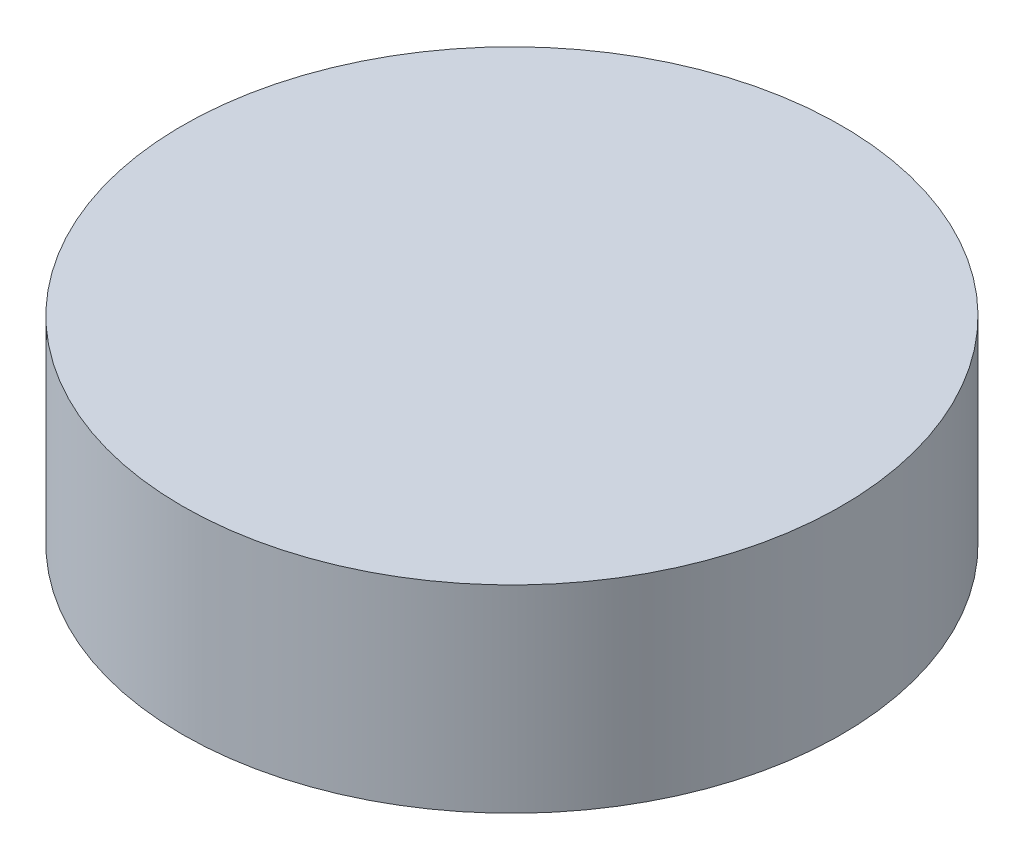
SolidWorks part; units mm, degrees
ref_plane "前视基准面" through (0, 0, 0) normal (0, 0, 1) x (1, 0, 0)
ref_plane "上视基准面" through (0, 0, 0) normal (0, 1, 0) x (1, 0, 0)
ref_plane "右视基准面" through (0, 0, 0) normal (1, 0, 0) x (0, 0, -1)
sketch "草图1" plane through (0, 0, 0) normal (0, 1, 0) x (1, 0, 0)
  circle A0 centre (0, 0) radius 20
  dimension "D1" = 40
extrude "凸台-拉伸1" add sketch "草图1" along normal blind 12
